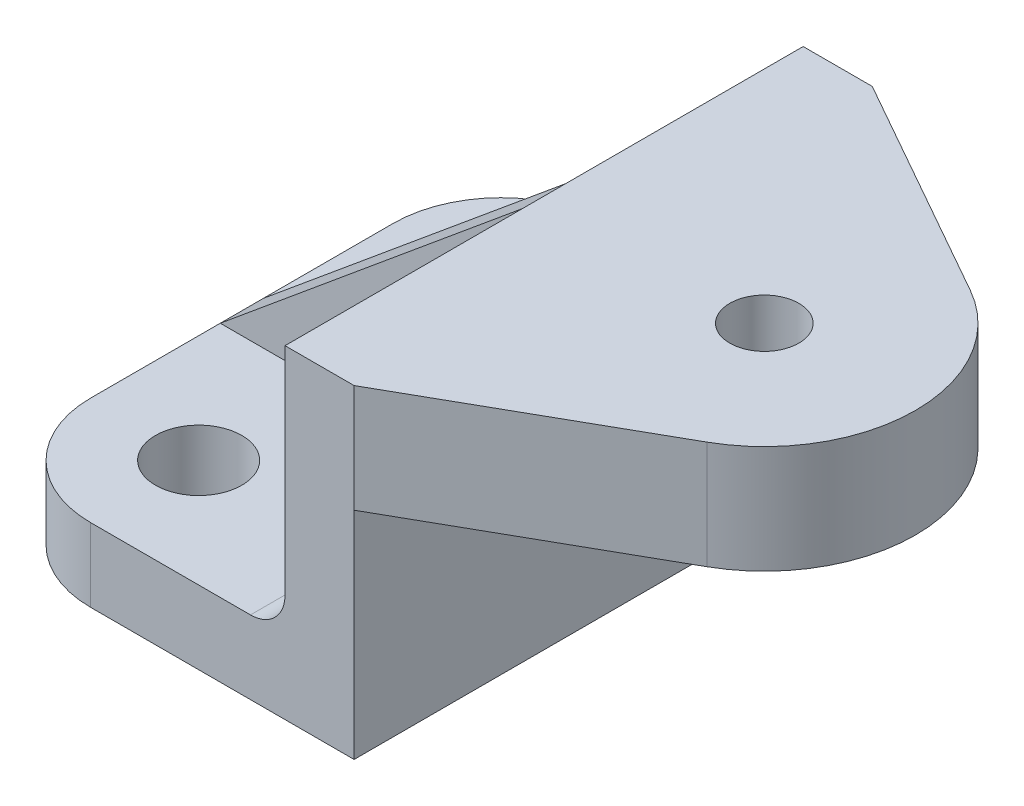
SolidWorks part; units mm, degrees
ref_plane "Front Plane" through (0, 0, 0) normal (0, 0, 1) x (1, 0, 0)
ref_plane "Top Plane" through (0, 0, 0) normal (0, 1, 0) x (1, 0, 0)
ref_plane "Right Plane" through (0, 0, 0) normal (1, 0, 0) x (0, 0, -1)
sketch "Sketch3" plane through (0, 0, 0) normal (1, 0, 0) x (0, 0, -1)
  line L1 (0, 0) -> (120, 0)
  line L2 (0, 0) -> (0, 17)
  line L3 (0, 17) -> (120, 17)
  line L4 (120, 0) -> (120, 17)
  dimension "D1" = 120
  dimension "D2" = 17
extrude "Boss-Extrude1" add sketch "Sketch3" along normal blind 86
sketch "Sketch5" plane through (86, 0, 0) normal (1, 0, 0) x (0, 0, -1)
  line L1 (0, 0) -> (120, 0)
  line L2 (0, 0) -> (0, 75)
  line L3 (0, 75) -> (120, 75)
  line L4 (120, 0) -> (120, 75)
  dimension "D1" = 120
  dimension "D2" = 75
extrude "Boss-Extrude2" add sketch "Sketch5" against normal blind 16
sketch "Sketch7" plane through (0, 75, 0) normal (0, 1, 0) x (1, 0, 0)
  line L0 (86, 60) -> (121, 60)
  line L1 (86, 120) -> (86, 0) construction
  line L2 (86, 120) -> (138.228, 90.4663)
  line L3 (86, 0) -> (138.228, 29.5337)
  circle A0 centre (121, 60) radius 35
  dimension "D2" = 70
  dimension "D1" = 35
extrude "Boss-Extrude3" add sketch "Sketch7" against normal blind 25
sketch "Sketch11" plane through (0, 75, 0) normal (0, 1, 0) x (1, 0, 0)
  line L0 (70, 60) -> (121, 60)
  line L1 (70, 0) -> (70, 120) construction
  circle A0 centre (121, 60) radius 8
  dimension "D2" = 16
  dimension "D1" = 51
extrude "Cut-Extrude1" cut sketch "Sketch11" against normal blind 25
fillet "Fillet2" radius 25 1 edges at (0, 8.5, 0)
fillet "Fillet3" radius 25 1 edges at (0, 8.5, -120)
fillet "Fillet11" radius 8 1 edges at (70, 17, -60)
sketch "Sketch14" plane through (0, 0, 0) normal (0, 0, 1) x (1, 0, 0)
  line L0 (70, 75) -> (0, 17)
  line L1 (0, 17) -> (70, 17)
  line L2 (70, 17) -> (70, 75)
extrude "Boss-Extrude4" add sketch "Sketch14" against normal blind 65 contours L0 L1 L2
sketch "Sketch15" plane through (0, 0, 0) normal (0, 0, 1) x (1, 0, 0)
  line L0 (0, 17) -> (70, 75)
  line L1 (70, 75) -> (70, 17)
  line L2 (70, 17) -> (0, 17)
extrude "Cut-Extrude2" cut sketch "Sketch15" against normal blind 55
fillet "Fillet15" radius 8 1 edges at (70, 17, -27.5)
sketch "Sketch16" plane through (0, 17, 0) normal (0, 1, 0) x (1, 0, 0)
  line L0 (0, 95) -> (25, 95)
  circle A0 centre (25, 95) radius 10
extrude "Cut-Extrude3" cut sketch "Sketch16" against normal blind 55
sketch "Sketch17" plane through (0, 17, 0) normal (0, 1, 0) x (1, 0, 0)
  circle A0 centre (25, 25) radius 10
extrude "Cut-Extrude4" cut sketch "Sketch17" against normal blind 55
